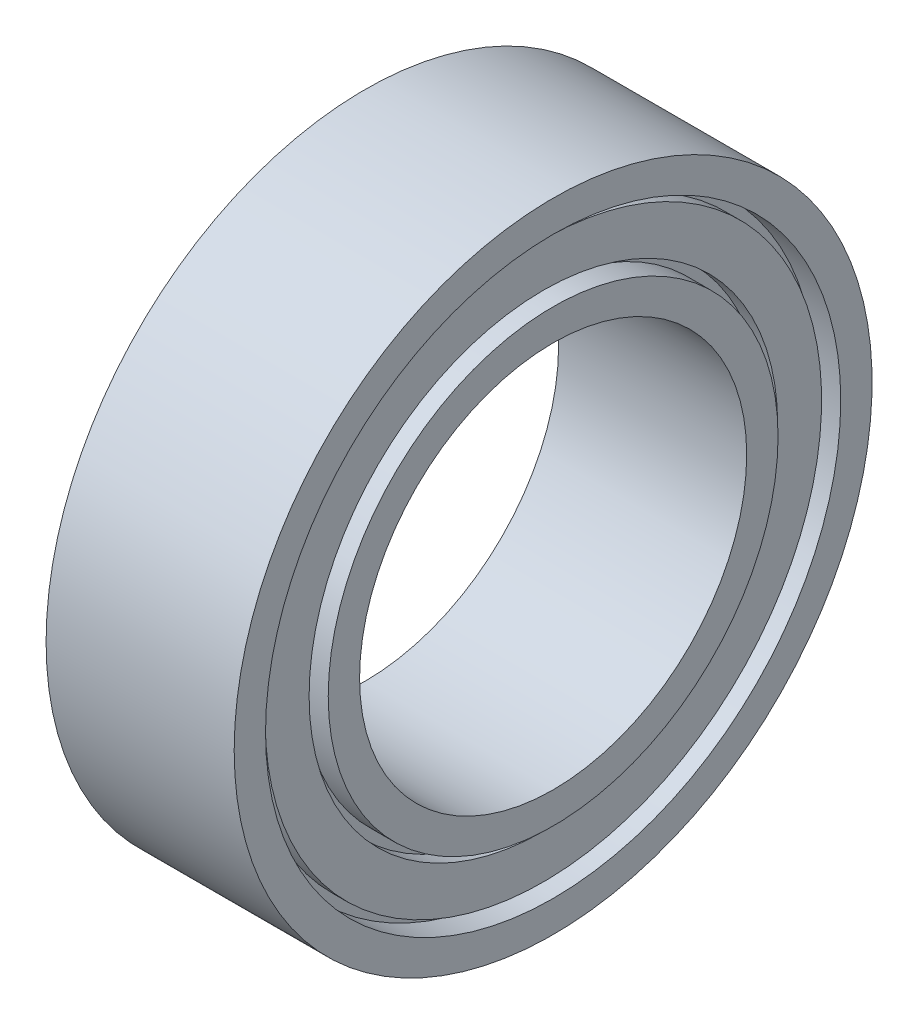
SolidWorks part; units mm, degrees
ref_plane "Front Plane" through (0, 0, 0) normal (0, 0, 1) x (1, 0, 0)
ref_plane "Top Plane" through (0, 0, 0) normal (0, 1, 0) x (1, 0, 0)
ref_plane "Right Plane" through (0, 0, 0) normal (1, 0, 0) x (0, 0, -1)
sketch "Sketch1" plane through (0, 0, 0) normal (0, 0, 1) x (1, 0, 0)
  line L0 (0, 0) -> (0, 3.0871) construction
  line L1 (0, 3.0871) -> (0, 5.0095) construction
  line L2 (0, 5.0095) -> (0, 6.2846) construction
  line L3 (-1.5, 3.0871) -> (1.5, 3.0871)
  line L4 (1.5, 3.0871) -> (1.5, 3.5871)
  line L5 (1.5, 3.5871) -> (1.1, 3.5871)
  line L6 (1.1, 3.5871) -> (1.1, 3.7371)
  line L7 (1.1, 3.7371) -> (1.3448, 3.7371)
  line L8 (1.3448, 3.7371) -> (1.3448, 4.4371)
  line L9 (1.3448, 4.4371) -> (1.1, 4.4371)
  line L10 (1.1, 4.4371) -> (1.1, 4.5871)
  line L11 (1.1, 4.5871) -> (1.5, 4.5871)
  line L12 (1.5, 4.5871) -> (1.5, 5.0871)
  line L13 (1.5, 5.0871) -> (-1.5, 5.0871)
  line L14 (-2.6792, 0) -> (2.6792, 0) construction
  line L15 (-1.5, 4.5871) -> (-1.5, 5.0871)
  line L16 (-1.1, 4.5871) -> (-1.5, 4.5871)
  line L17 (-1.1, 4.4371) -> (-1.1, 4.5871)
  line L18 (-1.3448, 4.4371) -> (-1.1, 4.4371)
  line L19 (-1.3448, 3.7371) -> (-1.3448, 4.4371)
  line L20 (-1.1, 3.7371) -> (-1.3448, 3.7371)
  line L21 (-1.1, 3.5871) -> (-1.1, 3.7371)
  line L22 (-1.5, 3.5871) -> (-1.1, 3.5871)
  line L23 (-1.5, 3.0871) -> (-1.5, 3.5871)
  point P18 (0, 5.0871)
  dimension "D1" = 1.5
  dimension "D2" = 2
  dimension "D3" = 0.5
  dimension "D4" = 0.5
  dimension "D5" = 0.15
  dimension "D6" = 0.15
  dimension "D7" = 0.4
  dimension "D8" = 0.4
revolve "Revolve1" add sketch "Sketch1" angle 360 about L14
